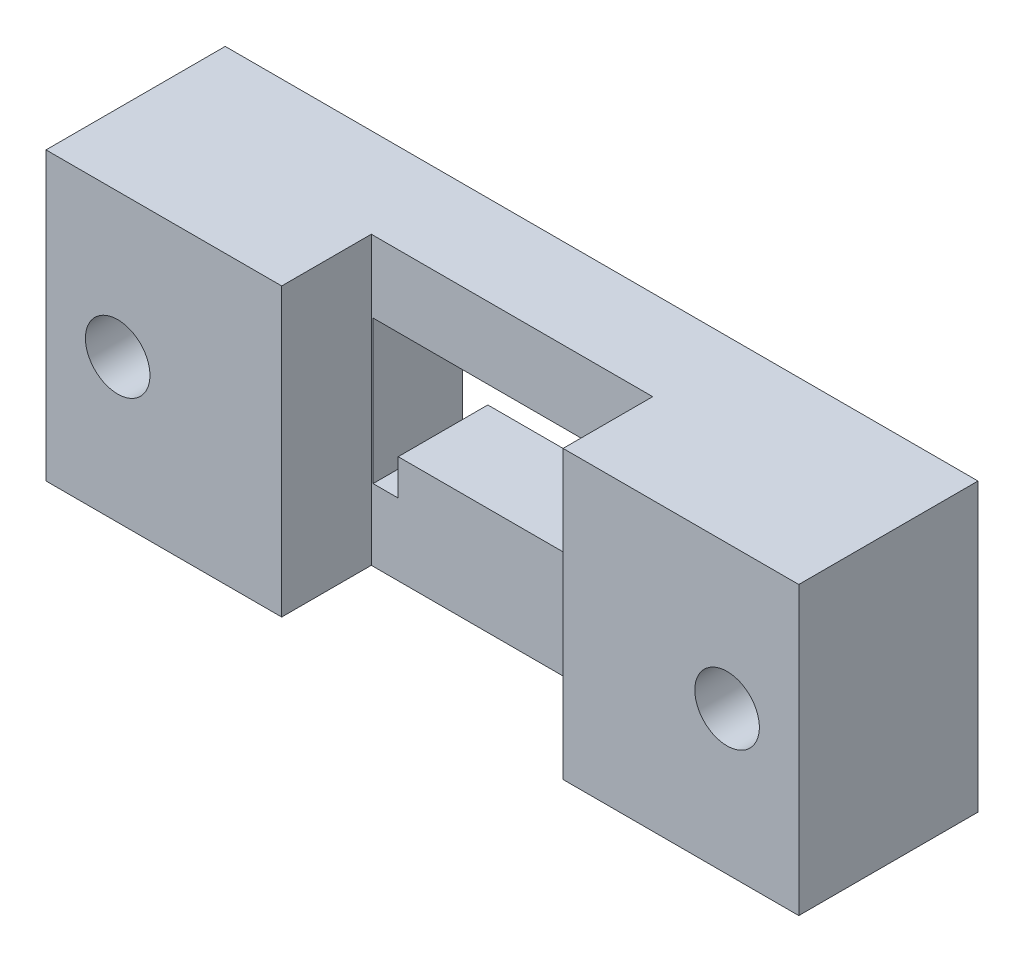
SolidWorks part; units mm, degrees
material "SKD11淬火HRC56-60"
ref_plane "前基準面" through (0, 0, 0) normal (0, 0, 1) x (1, 0, 0)
ref_plane "上基準面" through (0, 0, 0) normal (0, 1, 0) x (1, 0, 0)
ref_plane "右基準面" through (0, 0, 0) normal (1, 0, 0) x (0, 0, -1)
sketch "草图1" plane through (0, 0, 0) normal (0, 0, 1) x (1, 0, 0)
  line L1 (0, 0) -> (42, 0)
  line L2 (0, 0) -> (0, 16)
  line L3 (0, 16) -> (42, 16)
  line L4 (42, 0) -> (42, 16)
  dimension "D1" = 42
  dimension "D2" = 16
extrude "凸台-拉伸1" add sketch "草图1" along normal blind 10
sketch "草图2" plane through (0, 0, 10) normal (0, 0, 1) x (1, 0, 0)
  line L0 (21, 16) -> (21, 0) construction
  line L1 (42, 16) -> (0, 16) construction
  line L2 (0, 0) -> (42, 0) construction
  line L3 (28.75, 12) -> (13.25, 12)
  line L4 (13.25, 12) -> (13.25, 4)
  line L5 (13.25, 4) -> (14.65, 4)
  line L6 (14.65, 4) -> (14.65, 6)
  line L7 (14.65, 6) -> (27.35, 6)
  line L8 (27.35, 4) -> (27.35, 6)
  line L9 (28.75, 4) -> (27.35, 4)
  line L10 (28.75, 12) -> (28.75, 4)
  line L11 (0, 8) -> (42, 8) construction
  line L12 (0, 16) -> (0, 0) construction
  line L13 (42, 0) -> (42, 16) construction
  point P13 (21, 6)
  point P16 (21, 12)
  dimension "D1" = 15.5
  dimension "D2" = 8
  dimension "D3" = 2
  dimension "D4" = 1.4
extrude "切除-拉伸1" cut sketch "草图2" against normal through all
sketch "草图4" plane through (0, 0, 10) normal (0, 0, 1) x (1, 0, 0)
  line L0 (42, 16) -> (0, 16) construction
  line L1 (13.15, 16) -> (28.85, 16)
  line L2 (13.15, 16) -> (13.15, 0)
  line L3 (13.15, 0) -> (28.85, 0)
  line L4 (28.85, 16) -> (28.85, 0)
  line L5 (0, 0) -> (42, 0) construction
  line L6 (21, 16) -> (21, 0) construction
  dimension "D1" = 15.7
extrude "切除-拉伸2" cut sketch "草图4" against normal blind 5
hole_wizard "M3 六角凹头螺钉的柱形沉头孔1" positions "草图6" profile "草图5" counterbore size "M3" standard "ISO" end condition through all
sketch "草图6" plane through (0, 0, 0) normal (0, 0, -1) x (-1, 0, 0)
  line L0 (0, 8) -> (-42, 8) construction
  line L1 (0, 16) -> (0, 0) construction
  line L2 (-42, 0) -> (-42, 16) construction
  line L3 (-21, 16) -> (-21, 0) construction
  line L4 (-42, 16) -> (0, 16) construction
  line L5 (0, 0) -> (-42, 0) construction
  point P0 (-38, 8)
  point P1 (-4, 8)
  dimension "D1" = 34
sketch "草图5" plane through (38, 8, 0) normal (1, 0, 0) x (0, 1, 0)
  line L0 (0, 0) -> (0, 10)
  line L1 (0, 10) -> (1.8, 10)
  line L3 (1.8, 10) -> (1.8, 3)
  line L4 (1.8, 3) -> (3.25, 3)
  line L5 (3.25, 3) -> (3.25, 0)
  line L7 (3.25, 0) -> (0, 0)
  line L11 (0, -6.35) -> (0, 107.95) construction
  dimension "通孔孔直径" = 3.6
  dimension "通孔孔深度" = 10
  dimension "柱形沉头孔直径" = 6.5
  dimension "柱形沉头孔深度" = 3
